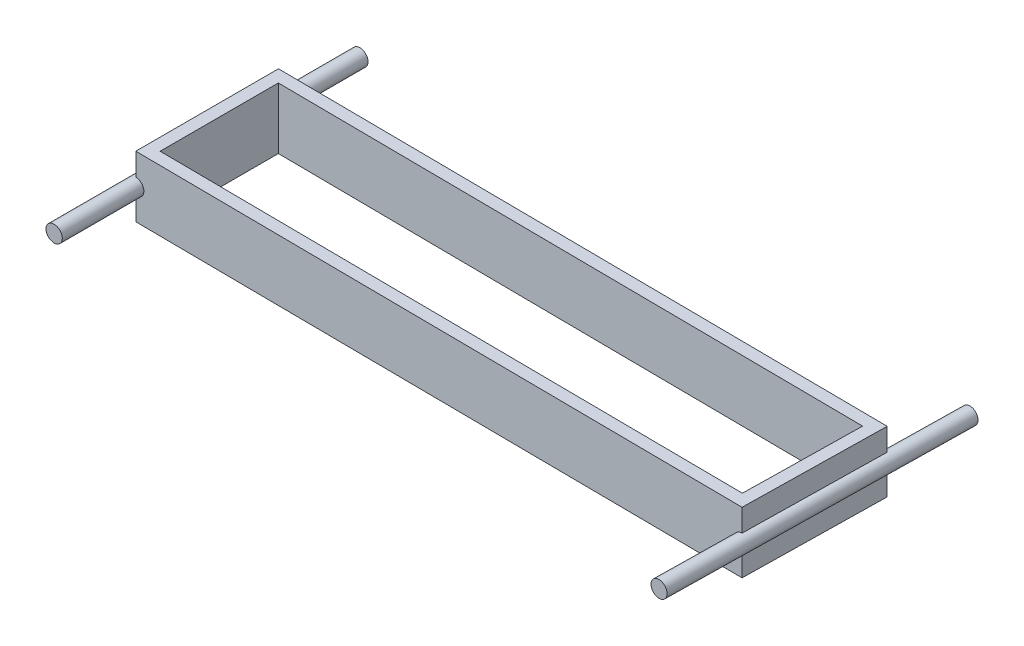
SolidWorks part; units mm, degrees
material "AISI 1020"
ref_plane "Front Plane" through (0, 0, 0) normal (0, 0, 1) x (1, 0, 0)
ref_plane "Top Plane" through (0, 0, 0) normal (0, 1, 0) x (1, 0, 0)
ref_plane "Right Plane" through (0, 0, 0) normal (1, 0, 0) x (0, 0, -1)
sketch "Sketch1" plane through (0, 0, 0) normal (0, 1, 0) x (1, 0, 0)
  line L1 (-323.5095, -44.3847) -> (57.4765, -47.6504)
  line L2 (-323.5095, -44.3847) -> (-323.5095, 44.5153)
  line L3 (-323.5095, 44.5153) -> (59.0004, 41.2365)
  line L4 (57.4765, -47.6504) -> (59.0004, 41.2365)
  line L5 (-315.8895, -36.8297) -> (49.9871, -39.9659)
  line L6 (-315.8895, -36.8297) -> (-315.8895, 36.8297)
  line L7 (-315.8895, 36.8297) -> (51.2498, 33.6827)
  line L8 (49.9871, -39.9659) -> (51.2498, 33.6827)
  line L9 (-1000, 0) -> (49000, 0) construction
  dimension "D1" = 7.62
  dimension "D2" = 7.62
  dimension "D3" = 7.62
  dimension "D4" = 7.62
  dimension "D5" = 88.9
  dimension "D6" = 382.524
  dimension "D7" = 381
extrude "Boss-Extrude1" add sketch "Sketch1" against normal blind 38.1
sketch "Sketch2" plane through (0, 0, 0) normal (0, 0, 1) x (1, 0, 0)
  line L1 (-323.5095, -38.1) -> (-323.5095, 0) construction
  circle A0 centre (-323.5095, -19.05) radius 5.08
  point P4 (-323.5095, -19.05)
  dimension "D1" = 10.16
extrude "Boss-Extrude2" add sketch "Sketch2" along normal mid plane 190.5
ref_plane "Plane2" through (-132.6124, 0, -1.1367) normal (1, 0, 0.0086) x (0.0086, 0, -1)
mirror "Mirror1" about plane through (-132.6124, 0, -1.1367) normal (1, 0, 0.0086) of "Boss-Extrude2"
